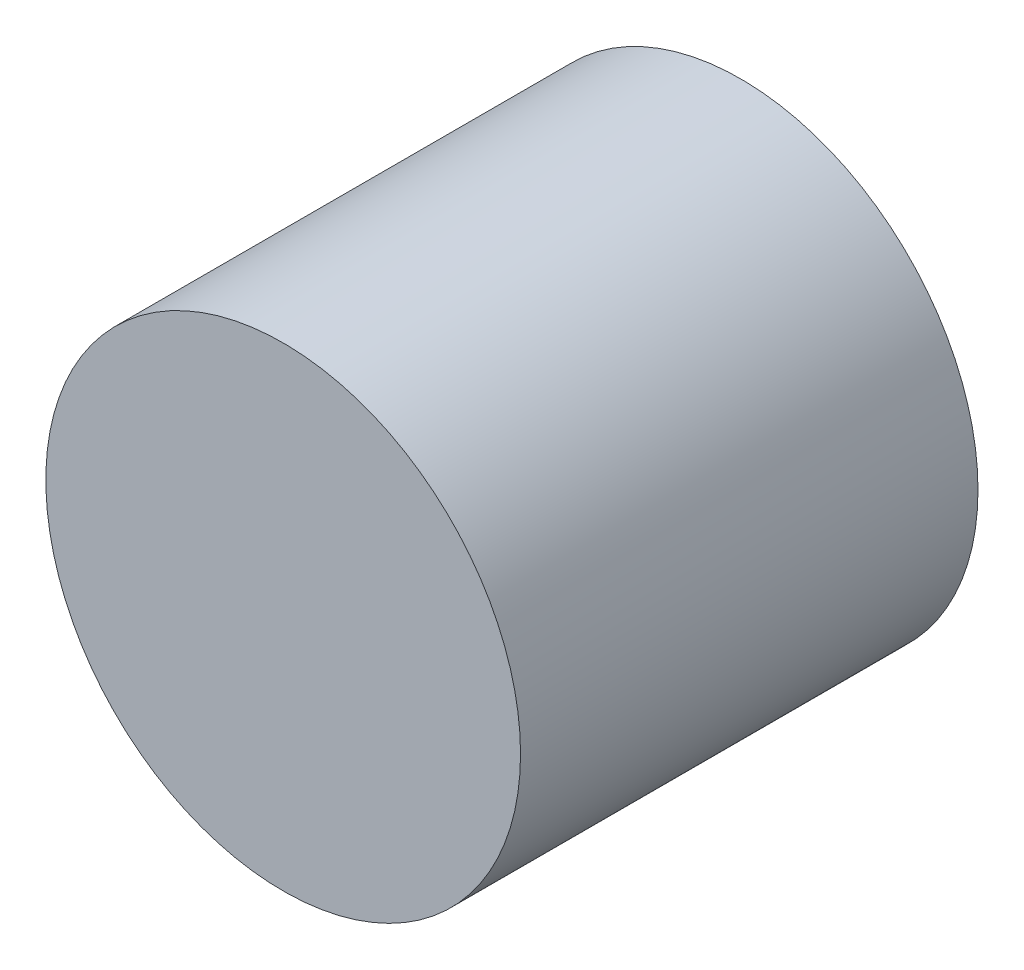
SolidWorks part; units mm, degrees
ref_plane "Front Plane" through (0, 0, 0) normal (0, 0, 1) x (1, 0, 0)
ref_plane "Top Plane" through (0, 0, 0) normal (0, 1, 0) x (1, 0, 0)
ref_plane "Right Plane" through (0, 0, 0) normal (1, 0, 0) x (0, 0, -1)
sketch "Sketch1" plane through (0, 0, 0) normal (0, 0, 1) x (1, 0, 0)
  circle A0 centre (0, 0) radius 13.75
extrude "Boss-Extrude1" add sketch "Sketch1" against normal blind 26.5
